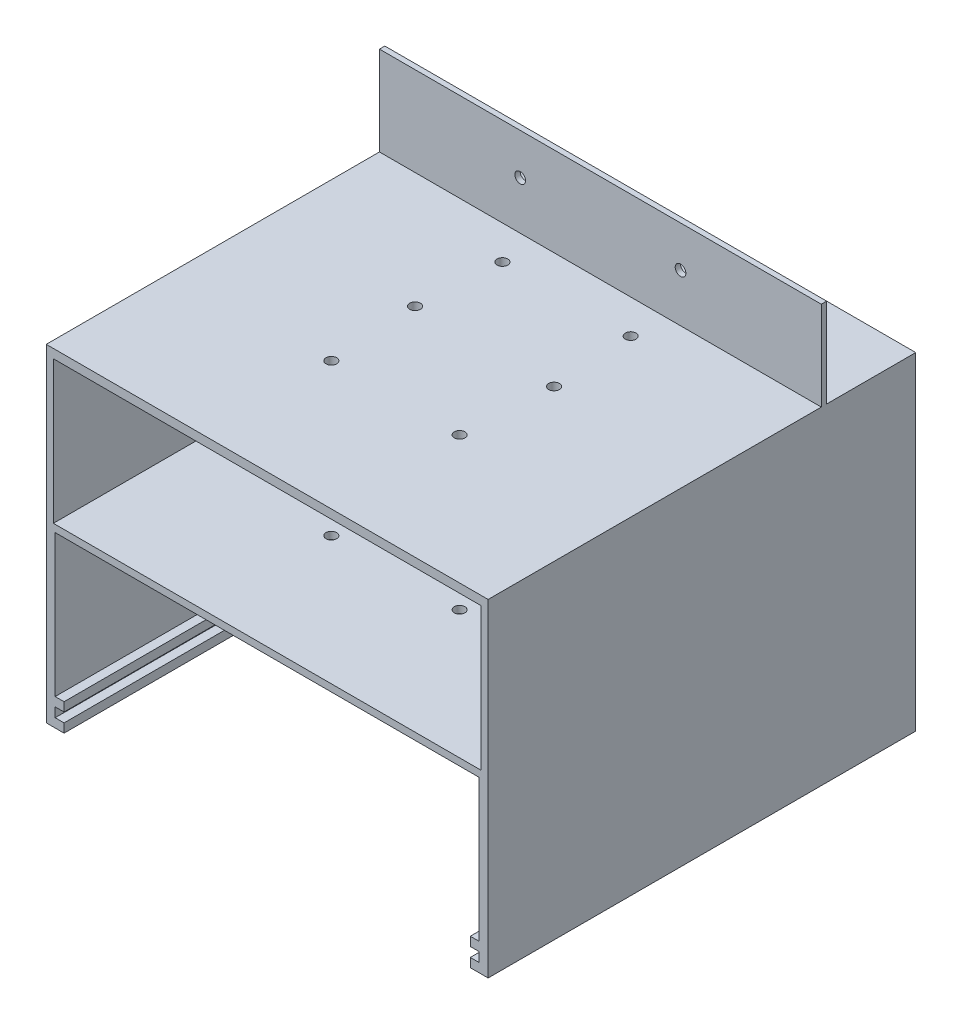
SolidWorks part; units mm, degrees
ref_plane "前视基准面" through (0, 0, 0) normal (0, 0, 1) x (1, 0, 0)
ref_plane "上视基准面" through (0, 0, 0) normal (0, 1, 0) x (1, 0, 0)
ref_plane "右视基准面" through (0, 0, 0) normal (1, 0, 0) x (0, 0, -1)
sketch "草图2" plane through (0, 0, 0) normal (0, 1, 0) x (1, 0, 0)
  line L1 (-62, 60) -> (62, 60)
  line L2 (-62, 60) -> (-62, -60)
  line L3 (-62, -60) -> (62, -60)
  line L4 (62, 60) -> (62, -60)
  line L5 (-62, 60) -> (62, -60) construction
  line L6 (-62, -60) -> (62, 60) construction
  point P0 (0, 0)
  dimension "D1" = 124
  dimension "D2" = 120
extrude "凸台-拉伸1" add sketch "草图2" along normal blind 2
sketch "草图3" plane through (0, 2, 0) normal (0, 1, 0) x (1, 0, 0)
  line L0 (-62, -60) -> (62, -60) construction
  line L1 (-62, 60) -> (-60, 60)
  line L2 (-62, 60) -> (-62, -60)
  line L3 (-62, -60) -> (-60, -60)
  line L4 (-60, 60) -> (-60, -60)
  line L6 (62, 60) -> (60, 60)
  line L7 (62, 60) -> (62, -60)
  line L8 (62, -60) -> (60, -60)
  line L9 (60, 60) -> (60, -60)
  dimension "D1" = 2
  dimension "D2" = 2
extrude "凸台-拉伸2" add sketch "草图3" along normal blind 40
sketch "草图4" plane through (0, 2, 0) normal (0, 1, 0) x (1, 0, 0)
  line L0 (60, 60) -> (60, -60) construction
  line L1 (-60, 60) -> (60, 60)
  line L2 (-60, 60) -> (-60, 58)
  line L3 (-60, 58) -> (60, 58)
  line L4 (60, 60) -> (60, 58)
  dimension "D1" = 2
extrude "凸台-拉伸3" add sketch "草图4" along normal blind 5
sketch "草图6" plane through (0, 42, 0) normal (0, 1, 0) x (1, 0, 0)
  line L1 (-62, 60) -> (62, 60)
  line L2 (-62, 60) -> (-62, -60)
  line L3 (-62, -60) -> (62, -60)
  line L4 (62, 60) -> (62, -60)
extrude "凸台-拉伸4" add sketch "草图6" along normal blind 2.5
sketch "草图9" plane through (0, 44.5, 0) normal (0, 1, 0) x (1, 0, 0)
  line L1 (-62, 60) -> (-62, -60) construction
  line L2 (-62, 35) -> (62, 35)
  line L3 (-62, 35) -> (-62, 33.5)
  line L4 (-62, 33.5) -> (62, 33.5)
  line L5 (62, 35) -> (62, 33.5)
  line L6 (62, -60) -> (62, 60) construction
  line L7 (62, 60) -> (-62, 60) construction
  dimension "D1" = 1.5
  dimension "D2" = 25
extrude "凸台-拉伸5" add sketch "草图9" along normal blind 25
sketch "草图10" plane through (0, 0, -35) normal (0, 0, -1) x (-1, 0, 0)
  line L0 (-37.3016, 58) -> (-44.8167, 58) construction
  line L4 (-62, 69.5) -> (62, 69.5) construction
  line L5 (0, 70.5) -> (0, 58) construction
  circle A0 centre (-22.5, 58) radius 1.5
  circle A1 centre (22.5, 58) radius 1.5
  point P6 (0, 69.5)
  dimension "D1" = 45
  dimension "D2" = 22.5
extrude "切除-拉伸2" cut sketch "草图10" against normal blind 1.5
sketch "草图11" plane through (0, 44.5, 0) normal (0, 1, 0) x (1, 0, 0)
  line L0 (0, 33.5) -> (0, 8.5131) construction
  line L2 (-62, 33.5) -> (62, 33.5) construction
  line L3 (-62, 33.5) -> (62, 33.5) construction
  circle A0 centre (-19.5, 1) radius 1.5
  circle A2 centre (-18, 24) radius 1.5
  circle A3 centre (-18, -24) radius 1.5
  circle A4 centre (18, -24) radius 1.5
  circle A5 centre (19.5, 1) radius 1.5
  circle A6 centre (18, 24) radius 1.5
  dimension "D1" = 19.5
  dimension "D3" = 9.5
  dimension "D2" = 32.5
  dimension "D4" = 48
  dimension "D5" = 18
  dimension "D6" = 18
extrude "切除-拉伸3" cut sketch "草图11" against normal blind 51
sketch "草图12" plane through (0, 0, 0) normal (0, -1, 0) x (1, 0, 0)
  line L0 (62, -60) -> (-62, -60) construction
  line L1 (-62, 60) -> (-59.5, 60)
  line L2 (-62, 60) -> (-62, -60)
  line L3 (-62, -60) -> (-59.5, -60)
  line L4 (-59.5, 60) -> (-59.5, -60)
  line L5 (-62, 60) -> (62, 60) construction
  line L6 (62, -60) -> (59.5, -60)
  line L7 (62, -60) -> (62, 60)
  line L8 (62, 60) -> (59.5, 60)
  line L9 (59.5, -60) -> (59.5, 60)
  dimension "D1" = 2.5
  dimension "D2" = 2.5
extrude "凸台-拉伸6" add sketch "草图12" along normal blind 47.5
sketch "草图14" plane through (0, 0, -60) normal (0, 0, -1) x (-1, 0, 0)
  line L1 (-59.5, -47.5) -> (-57, -47.5)
  line L2 (-59.5, -47.5) -> (-59.5, -45)
  line L3 (-59.5, -45) -> (-57, -45)
  line L4 (-57, -47.5) -> (-57, -45)
  line L5 (59.5, -47.5) -> (57, -47.5)
  line L6 (59.5, -47.5) -> (59.5, -45)
  line L7 (59.5, -45) -> (57, -45)
  line L8 (57, -47.5) -> (57, -45)
  dimension "D1" = 2.5
  dimension "D2" = 2.5
  dimension "D3" = 2.5
  dimension "D4" = 2.5
extrude "凸台-拉伸8" add sketch "草图14" against normal blind 120
sketch "草图15" plane through (0, 0, 0) normal (0, -1, 0) x (1, 0, 0)
  line L0 (59.5, 60) -> (59.5, -60) construction
  line L1 (-59.5, -60) -> (59.5, -60)
  line L2 (-59.5, -60) -> (-59.5, -57)
  line L3 (-59.5, -57) -> (59.5, -57)
  line L4 (59.5, -60) -> (59.5, -57)
  dimension "D1" = 3
extrude "凸台-拉伸9" add sketch "草图15" along normal blind 47.5
sketch "草图16" plane through (-62, 0, 0) normal (-1, 0, 0) x (0, 0, 1)
  line L5 (39.7788, -10.5) -> (13.9482, -10.5) construction
  circle A2 centre (2.7788, 31.3663) radius 2.5
  circle A3 centre (2.7788, -33.6337) radius 2.5
  dimension "D3" = 65
extrude "切除-拉伸4" cut sketch "草图16" against normal blind 10
sketch "草图18" plane through (0, 0, 60) normal (0, 0, 1) x (1, 0, 0)
  line L0 (-59.5, -45) -> (-59.5, 0) construction
  line L1 (-59.5, -45) -> (-57, -45) construction
  line L2 (-59.5, -42.35) -> (-57, -42.35)
  line L3 (-59.5, -42.35) -> (-59.5, -39.85)
  line L4 (-59.5, -39.85) -> (-57, -39.85)
  line L5 (-57, -42.35) -> (-57, -39.85)
  line L6 (59.5, -45) -> (59.5, 0) construction
  line L7 (59.5, -42.35) -> (57, -42.35)
  line L8 (59.5, -42.35) -> (59.5, -39.85)
  line L9 (59.5, -39.85) -> (57, -39.85)
  line L10 (57, -42.35) -> (57, -39.85)
  line L11 (59.5, -45) -> (57, -45) construction
  dimension "D1" = 2.5
  dimension "D2" = 2.5
  dimension "D3" = 2.65
  dimension "D4" = 2.5
  dimension "D5" = 2.5
  dimension "D6" = 2.65
extrude "凸台-拉伸10" add sketch "草图18" against normal blind 120
